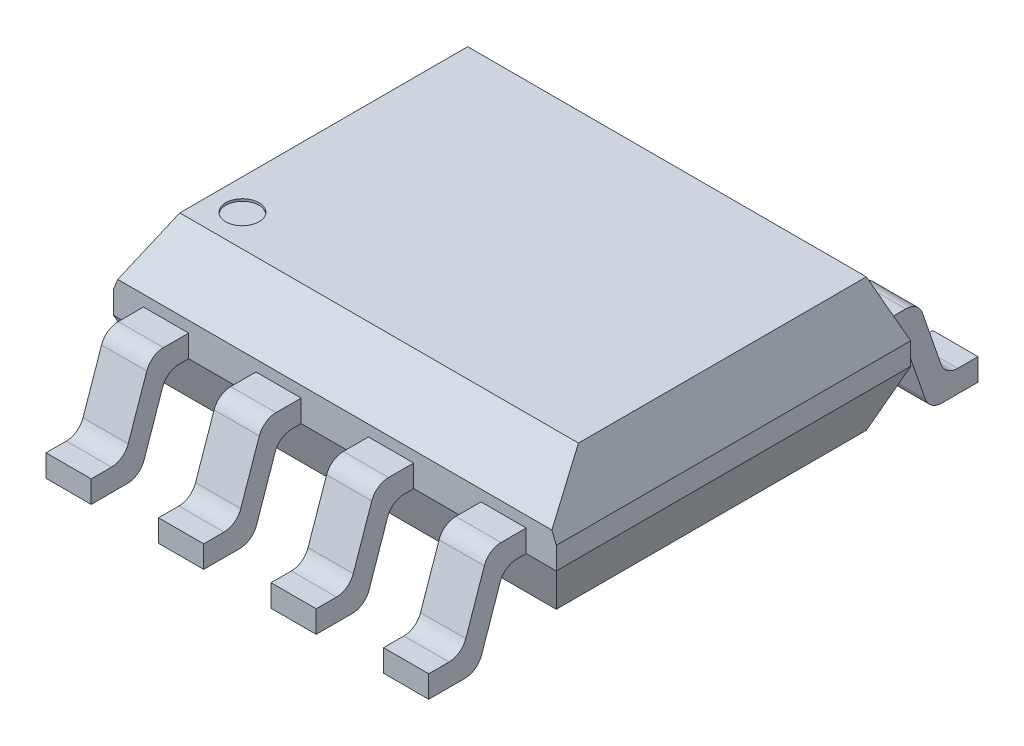
SolidWorks part; units mm, degrees
ref_plane "Front" through (0, 0, 0) normal (0, 0, 1) x (1, 0, 0)
ref_plane "Top" through (0, 0, 0) normal (0, 1, 0) x (1, 0, 0)
ref_plane "Right" through (0, 0, 0) normal (1, 0, 0) x (0, 0, -1)
sketch "Sketch1" plane through (0, 0, 0) normal (0, 1, 0) x (1, 0, 0)
  line L1 (-2.5, 2) -> (2.5, 2)
  line L2 (-2.5, 2) -> (-2.5, -2)
  line L3 (-2.5, -2) -> (2.5, -2)
  line L4 (2.5, 2) -> (2.5, -2)
  line L5 (-2.5, 2) -> (2.5, -2) construction
  line L6 (-2.5, -2) -> (2.5, 2) construction
  point P0 (0, 0)
  dimension "D1" = 5
  dimension "D2" = 4
extrude "Boss-Extrude1" add sketch "Sketch1" along normal offset from surface (1.5 mm away) 1.75 from offset 0.25 up to plane "Top"
sketch "Sketch2" plane through (0, 0, 2) normal (0, 0, 1) x (1, 0, 0)
  line L0 (-2.5, 1.75) -> (-2.25, 1.75)
  line L1 (-2.5, 1.75) -> (2.5, 1.75) construction
  line L2 (-2.25, 1.75) -> (-2.5, 1.125)
  line L3 (-2.5, 1.75) -> (-2.5, 0.25) construction
  line L4 (-2.5, 1.125) -> (-2.5, 1.75)
  line L5 (-2.5, 1) -> (2.5, 1) construction
  line L6 (2.5, 1.75) -> (2.5, 0.25) construction
  line L7 (0, 1.75) -> (0, 0.25) construction
  line L8 (-2.5, 0.25) -> (2.5, 0.25) construction
  line L9 (-2.5, 0.875) -> (-2.5, 0.25)
  line L10 (-2.25, 0.25) -> (-2.5, 0.875)
  line L11 (-2.5, 0.25) -> (-2.25, 0.25)
  line L12 (2.5, 0.25) -> (2.25, 0.25)
  line L13 (2.25, 0.25) -> (2.5, 0.875)
  line L14 (2.5, 0.875) -> (2.5, 0.25)
  line L15 (2.5, 1.125) -> (2.5, 1.75)
  line L16 (2.25, 1.75) -> (2.5, 1.125)
  line L17 (2.5, 1.75) -> (2.25, 1.75)
  dimension "D1" = 0.125
  dimension "D2" = 0.25
extrude "Cut-Extrude1" cut sketch "Sketch2" against normal through all
sketch "Sketch3" plane through (-2.5, 0, 0) normal (-1, 0, 0) x (0, 0, 1)
  line L0 (1.5, 1.75) -> (2, 1.25)
  line L1 (-2, 1.75) -> (2, 1.75) construction
  line L2 (2, 1.125) -> (2, 1.75) construction
  line L3 (2, 0.875) -> (1.75, 0.25)
  line L4 (-2, 0.25) -> (2, 0.25) construction
  line L5 (1.75, 0.25) -> (2, 0.25)
  line L6 (2, 0.25) -> (2, 0.875)
  line L7 (1.5, 1.75) -> (2, 1.75)
  line L8 (2, 1.75) -> (2, 1.25)
  line L9 (0, 1.75) -> (0, 0.25) construction
  line L10 (-2, 0.25) -> (-2, 0.875)
  line L11 (-1.75, 0.25) -> (-2, 0.25)
  line L12 (-2, 0.875) -> (-1.75, 0.25)
  line L13 (-2, 1) -> (0, 1) construction
  line L14 (-2, 1.125) -> (-2, 0.875) construction
  line L15 (-2, 1.125) -> (-1.75, 1.75)
  line L16 (-1.75, 1.75) -> (-2, 1.75)
  line L17 (-2, 1.75) -> (-2, 1.125)
  dimension "D1" = 0.25
  dimension "D2" = 0.5
extrude "Cut-Extrude2" cut sketch "Sketch3" against normal through all
sketch "Sketch4" plane through (0, 1.75, 0) normal (0, 1, 0) x (1, 0, 0)
  line L0 (2.25, -1.5) -> (-2.25, -1.5) construction
  circle A0 centre (-1.903, -1.14) radius 0.1871
  dimension "D3" = 0.3743
  dimension "D1" = 0.5
  dimension "D2" = 0.36
extrude "Cut-Extrude3" cut sketch "Sketch4" against normal blind 0.0254
sketch "Sketch5" plane through (2.5, 0, 0) normal (1, 0, 0) x (0, 0, -1)
  line L0 (2, 1.125) -> (2.4265, 1.125)
  line L1 (2.4265, 1.125) -> (2.7282, 0.25)
  line L2 (2.7282, 0.25) -> (3.1, 0.25)
  line L3 (3.1, 0.25) -> (3.1, 0)
  line L4 (3.1, 0) -> (2.55, 0)
  line L5 (2.55, 0) -> (2.248, 0.8757)
  line L6 (2.248, 0.8757) -> (2, 0.875)
  line L7 (2, 0.875) -> (2, 1.125)
  line L8 (2.399, 0.4379) -> (2.6353, 0.5194) construction
  dimension "D1" = 0.55
  dimension "D2" = 3.1
  dimension "D3" = 0.248
  dimension "D4" = 108.865
extrude "Boss-Extrude3" add sketch "Sketch5" against normal up to vertex (5 mm away) separate body up to point (-2.5, 0.875, -2)
fillet "Fillet1" radius 0.2 4 edges at (0, 0.8757, -2.248) (0, 0, -2.55) (0, 0.25, -2.7282) (0, 1.125, -2.4265)
sketch "Sketch7" plane through (0, 1.75, 0) normal (0, 1, 0) x (1, 0, 0)
  line L0 (2.5, 2) -> (-2.5, 2) construction
  line L1 (-2.5, 3.1) -> (-2.16, 3.1)
  line L2 (-2.5, 3.1) -> (-2.5, 2)
  line L3 (-2.5, 2) -> (-2.16, 2)
  line L4 (-2.16, 3.1) -> (-2.16, 2)
  line L5 (-2.5, 3.1) -> (2.5, 3.1) construction
  line L6 (-1.65, 3.1) -> (-0.89, 3.1)
  line L7 (-1.65, 3.1) -> (-1.65, 2)
  line L8 (-1.65, 2) -> (-0.89, 2)
  line L9 (-0.89, 3.1) -> (-0.89, 2)
  line L10 (-1.65, 2.55) -> (-2.16, 2.55) construction
  line L11 (-0.38, 3.1) -> (0.38, 3.1)
  line L12 (-0.38, 3.1) -> (-0.38, 2)
  line L13 (-0.38, 2) -> (0.38, 2)
  line L14 (0.38, 3.1) -> (0.38, 2)
  line L15 (0.89, 3.1) -> (1.65, 3.1)
  line L16 (0.89, 3.1) -> (0.89, 2)
  line L17 (0.89, 2) -> (1.65, 2)
  line L18 (1.65, 3.1) -> (1.65, 2)
  line L19 (2.16, 3.1) -> (2.5, 3.1)
  line L20 (2.16, 3.1) -> (2.16, 2)
  line L21 (2.16, 2) -> (2.5, 2)
  line L22 (2.5, 3.1) -> (2.5, 2)
  line L23 (-0.89, 2.55) -> (-0.38, 2.55) construction
  line L24 (0.38, 2.55) -> (0.89, 2.55) construction
  line L25 (1.65, 2.55) -> (2.16, 2.55) construction
  line L26 (-0.635, 2.55) -> (0.635, 2.55) construction
  line L27 (-1.905, 2.55) -> (-0.635, 2.55) construction
  line L28 (0.635, 2.55) -> (1.905, 2.55) construction
  dimension "D1" = 0.51
  dimension "D2" = 1.27
extrude "Cut-Extrude4" cut sketch "Sketch7" against normal through all
mirror "Mirror1" about plane through (0, 0, 0) normal (0, 0, 1) of bodies 108 107 110 109
